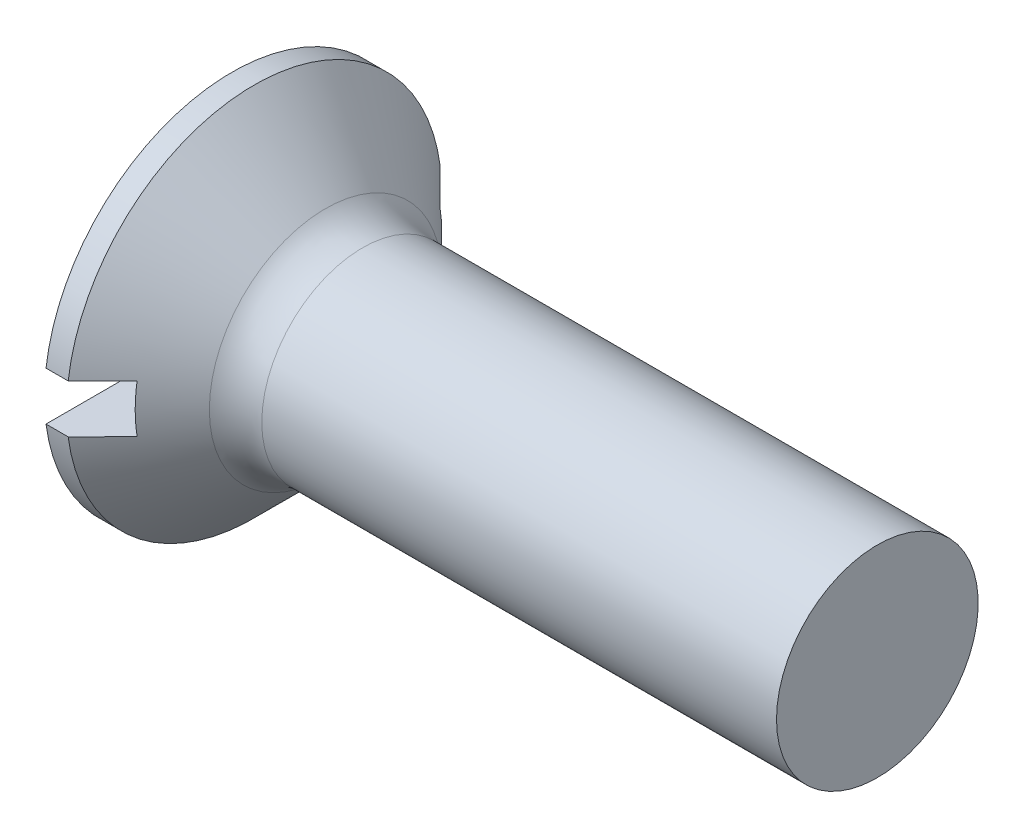
SolidWorks part; units mm, degrees
revolve "Base-Revolve" add sketch "BodySke" angle 360 about L5
sketch "BodySke" plane through (0, 0, 0) normal (0, 0, 1) x (1, 0, 0)
  line L0 (0, 0) -> (0, 4.65)
  line L1 (0, 4.65) -> (0.55, 4.65)
  line L2 (2.7, 2.5) -> (16, 2.5)
  line L3 (16, 2.5) -> (16, 0)
  line L4 (16, 0) -> (0, 0)
  line L5 (-6.35, 0) -> (82.55, 0) construction
  line L6 (2.7, -2.5) -> (16, -2.5) construction
  line L7 (0.55, -4.65) -> (2.7, -2.5) construction
  line L8 (0.55, 4.65) -> (2.7, 2.5)
  line L9 (0, -4.65) -> (0.55, -4.65) construction
  line L10 (3.5, 4.0875) -> (3.5, -5.4375) construction
  line L11 (0, 6.35) -> (0, -3.175) construction
  dimension "Diameter" = 5
  dimension "Length" = 16
  dimension "Head_ht" = 2.7
  dimension "Head_dia" = 9.3
  dimension "Head_ang" = 90
  dimension "D6" = 0.55
  dimension "Advance" = 0.8
  dimension "Thread_nom" = 16
cosmetic thread "ThreadCosmetic" [suppressed] parameters "Thread_length"=12.5, "Thread_minor"=4.11
extrude "Slot" cut sketch "Sketch2" against normal blind 1.4
sketch "Sketch2" plane through (0, 0, 0) normal (-1, 0, 0) x (0, 0, 1)
  line L0 (-4.65, -0.6) -> (4.65, -0.6)
  line L1 (-4.65, -0.6) -> (-4.65, 0.6)
  line L2 (4.65, 0.6) -> (-4.65, 0.6)
  line L3 (4.65, 0.6) -> (4.65, -0.6)
  dimension "Slot_width" = 1.2
  dimension "D1" = 0.6
  dimension "D2" = 9.3
  dimension "D3" = 4.65
ref_plane "Plane1" through (0, 0, 0) normal (0, 0, 1) x (1, 0, 0)
ref_plane "Plane2" through (0, 0, 0) normal (0, 1, 0) x (1, 0, 0)
ref_plane "Plane3" through (0, 0, 0) normal (1, 0, 0) x (0, 0, -1)
fillet "Fillet1" radius 1.3 1 edges at (2.7, 0, 2.5)
sketch "ThdSchSke" plane through (0, 0, 0) normal (0, 0, 1) x (1, 0, 0)
  line L0 (3.5, -2.055) -> (3.1884, -2.5)
  line L1 (3.5, -2.055) -> (3.8116, -2.5)
  line L2 (3.8116, -2.5) -> (3.8116, -3.125)
  line L3 (-3.175, 0) -> (5.1513, 0) construction
  line L5 (3.8116, -3.125) -> (3.1884, -3.125)
  line L6 (3.1884, -3.125) -> (3.1884, -2.5)
  line L7 (0, 4.65) -> (0, 0.6) construction
  dimension "Diameter" = 5
  dimension "Thread_minor" = 4.11
  dimension "Start" = 3.5
revolve "ThreadSchematic" [suppressed] cut sketch "ThdSchSke" angle 360 about L3
pattern_linear "ThdSchPat" [suppressed]
equation "\"D1@Sketch2\" = \"Slot_width@Sketch2\" / 2"
equation "\"D2@Sketch2\" = \"Head_dia@BodySke\""
equation "\"D3@Sketch2\" = \"D2@Sketch2\" / 2"
equation "\"Thread_length@ThreadCosmetic\" = ((sgn( (\"Length@BodySke\" - \"Advance@BodySke\" * 1.0 - \"Head_ht@BodySke\" ) - \"Thread_nom@BodySke\" )-1)*( (\"Length@BodySke\" - \"Advance@BodySke\" * 1.0 - \"Head_ht@BodySke\" ) - \"Thread_nom@BodySke\" ))/-2+ \"Thread_nom@BodySke\""
equation "\"Thread_minor@ThdSchSke\" = \"Thread_minor@ThreadCosmetic\""
equation "\"Diameter@ThdSchSke\" = \"Diameter@BodySke\""
equation "\"Overcut@ThdSchSke\" = \"Diameter@BodySke\" * 1.25"
equation "\"Start@ThdSchSke\" = 0.000001 + \"Length@BodySke\" - \"Thread_length@ThreadCosmetic\"  '---Countersunk---"
equation "\"Num_threads@ThdSchPat\" = int( \"Thread_length@ThreadCosmetic\" / \"Advance@BodySke\" + 0.999 )  + 1"
equation "\"Advance@ThdSchPat\" = \"Thread_length@ThreadCosmetic\" /  (\"Num_threads@ThdSchPat\" - 1) 'relax it"
